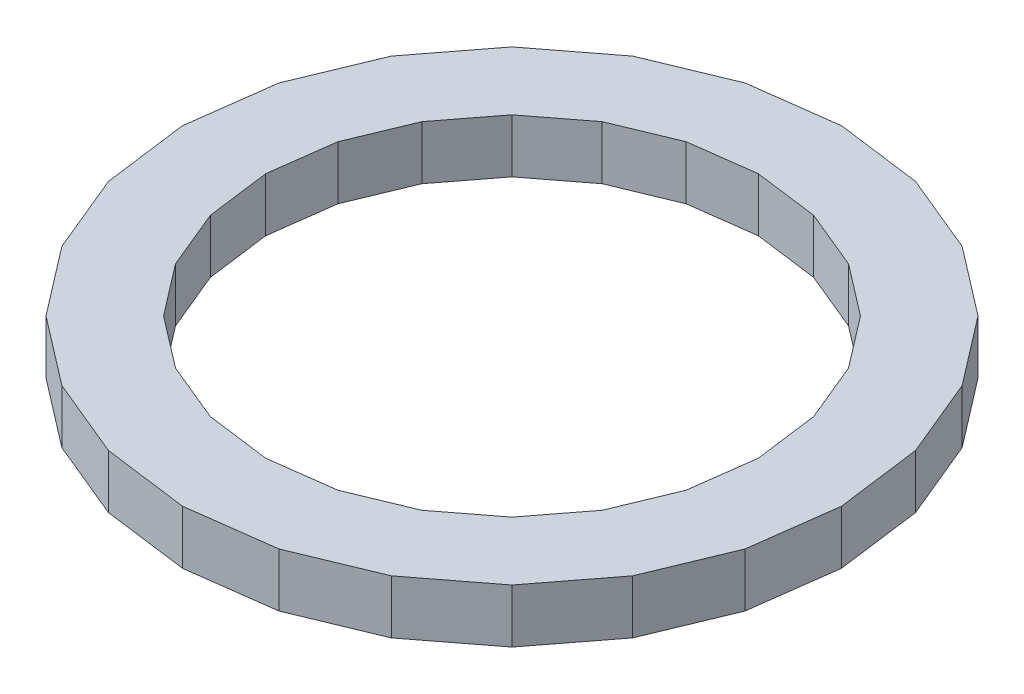
SolidWorks part; units mm, degrees
ref_plane "Front Plane" through (0, 0, 0) normal (0, 0, 1) x (1, 0, 0)
ref_plane "Top Plane" through (0, 0, 0) normal (0, 1, 0) x (1, 0, 0)
ref_plane "Right Plane" through (0, 0, 0) normal (1, 0, 0) x (0, 0, -1)
sketch "Sketch1" plane through (0, 0, 0) normal (0, 1, 0) x (1, 0, 0)
  line L0 (0, 0) -> (-87.2961, 0) construction
  line L1 (0, -116.7582) -> (30.2192, -112.7797)
  line L2 (30.2192, -112.7797) -> (58.3791, -101.1155)
  line L3 (58.3791, -101.1155) -> (82.5605, -82.5605)
  line L4 (82.5605, -82.5605) -> (101.1155, -58.3791)
  line L5 (101.1155, -58.3791) -> (112.7797, -30.2192)
  line L6 (112.7797, -30.2192) -> (116.7582, 0)
  line L7 (116.7582, 0) -> (112.7797, 30.2192)
  line L8 (112.7797, 30.2192) -> (101.1155, 58.3791)
  line L9 (101.1155, 58.3791) -> (82.5605, 82.5605)
  line L10 (82.5605, 82.5605) -> (58.3791, 101.1155)
  line L11 (58.3791, 101.1155) -> (30.2192, 112.7797)
  line L12 (30.2192, 112.7797) -> (0, 116.7582)
  line L13 (0, 116.7582) -> (-30.2192, 112.7797)
  line L14 (-30.2192, 112.7797) -> (-58.3791, 101.1155)
  line L15 (-58.3791, 101.1155) -> (-82.5605, 82.5605)
  line L16 (-82.5605, 82.5605) -> (-101.1155, 58.3791)
  line L17 (-101.1155, 58.3791) -> (-112.7797, 30.2192)
  line L18 (-112.7797, 30.2192) -> (-116.7582, 0)
  line L19 (-116.7582, 0) -> (-112.7797, -30.2192)
  line L20 (-112.7797, -30.2192) -> (-101.1155, -58.3791)
  line L21 (-101.1155, -58.3791) -> (-82.5605, -82.5605)
  line L22 (-82.5605, -82.5605) -> (-58.3791, -101.1155)
  line L23 (-58.3791, -101.1155) -> (-30.2192, -112.7797)
  line L24 (-30.2192, -112.7797) -> (0, -116.7582)
  line L25 (0, -87.2961) -> (22.5939, -84.3216)
  line L26 (22.5939, -84.3216) -> (43.6481, -75.6007)
  line L27 (43.6481, -75.6007) -> (61.7277, -61.7277)
  line L28 (61.7277, -61.7277) -> (75.6007, -43.6481)
  line L29 (75.6007, -43.6481) -> (84.3216, -22.5939)
  line L30 (84.3216, -22.5939) -> (87.2961, 0)
  line L31 (87.2961, 0) -> (84.3216, 22.5939)
  line L32 (84.3216, 22.5939) -> (75.6007, 43.6481)
  line L33 (75.6007, 43.6481) -> (61.7277, 61.7277)
  line L34 (61.7277, 61.7277) -> (43.6481, 75.6007)
  line L35 (43.6481, 75.6007) -> (22.5939, 84.3216)
  line L36 (22.5939, 84.3216) -> (0, 87.2961)
  line L37 (0, 87.2961) -> (-22.5939, 84.3216)
  line L38 (-22.5939, 84.3216) -> (-43.6481, 75.6007)
  line L39 (-43.6481, 75.6007) -> (-61.7277, 61.7277)
  line L40 (-61.7277, 61.7277) -> (-75.6007, 43.6481)
  line L41 (-75.6007, 43.6481) -> (-84.3216, 22.5939)
  line L42 (-84.3216, 22.5939) -> (-87.2961, 0)
  line L43 (-87.2961, 0) -> (-84.3216, -22.5939)
  line L44 (-84.3216, -22.5939) -> (-75.6007, -43.6481)
  line L45 (-75.6007, -43.6481) -> (-61.7277, -61.7277)
  line L46 (-61.7277, -61.7277) -> (-43.6481, -75.6007)
  line L47 (-43.6481, -75.6007) -> (-22.5939, -84.3216)
  line L48 (-22.5939, -84.3216) -> (0, -87.2961)
  line L49 (-116.7582, 0) -> (-87.2961, 0) construction
  circle A1 centre (0, 0) radius 115.7593 construction
  circle A2 centre (0, 0) radius 86.5493 construction
  dimension "D1" = 29.21
  dimension "D2" = 30.48
extrude "Boss-Extrude1" add sketch "Sketch1" along normal blind 19.05
